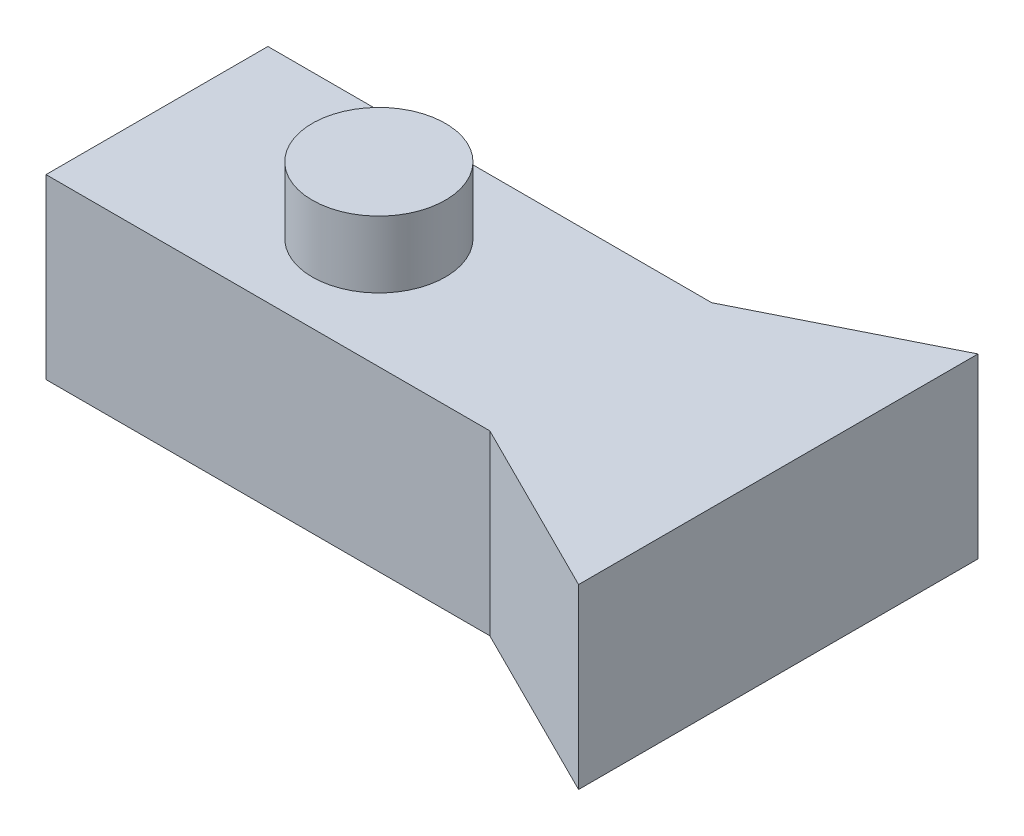
SolidWorks part; units mm, degrees
ref_plane "Front Plane" through (0, 0, 0) normal (0, 0, 1) x (1, 0, 0)
ref_plane "Top Plane" through (0, 0, 0) normal (0, 1, 0) x (1, 0, 0)
ref_plane "Right Plane" through (0, 0, 0) normal (1, 0, 0) x (0, 0, -1)
sketch "Sketch1" plane through (0, 0, 0) normal (0, 1, 0) x (1, 0, 0)
  line L0 (1000, 500) -> (1400, 700)
  line L1 (0, 0) -> (1000, 0)
  line L2 (0, 0) -> (0, 500)
  line L3 (0, 500) -> (1000, 500)
  line L4 (1000, 0) -> (1000, 500)
  line L5 (1400, 700) -> (1400, -200)
  line L6 (1400, -200) -> (1000, 0)
  line L7 (0, 0) -> (1000, 500) construction
  line L8 (0, 500) -> (1000, 0) construction
  dimension "D1" = 1000
  dimension "D2" = 500
  dimension "D3" = 400
extrude "Boss-Extrude1" add sketch "Sketch1" along normal blind 400 contours L6 L5 L0 L4 | L1 L4 L3 L2
sketch "Sketch2" plane through (0, 400, 0) normal (0, 1, 0) x (1, 0, 0)
  line L0 (0, 0) -> (1000, 500) construction
  line L1 (0, 500) -> (1000, 0) construction
  circle A0 centre (500, 250) radius 150
  point P10 (0, 0)
  dimension "D1" = 300
extrude "Boss-Extrude2" add sketch "Sketch2" along normal blind 150
